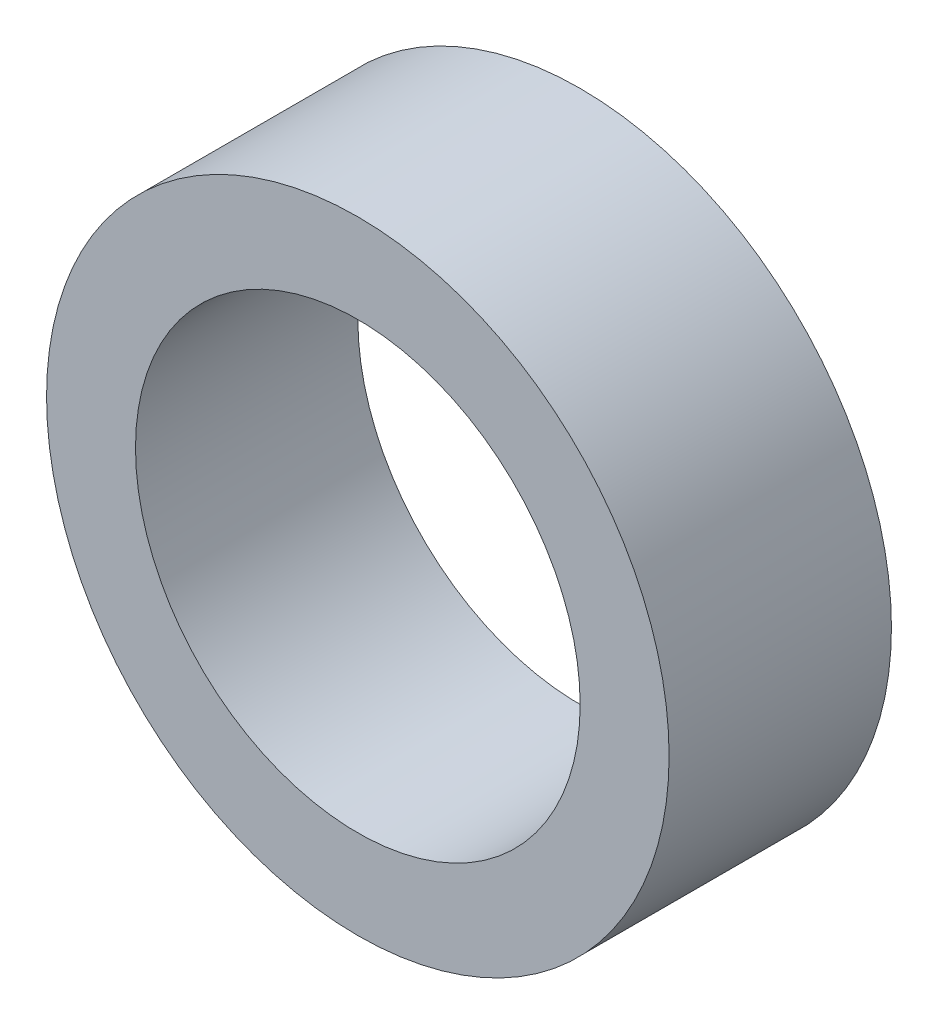
SolidWorks part; units mm, degrees
material "High-leaded brass, UNS C34200"
ref_plane "Front Plane" through (0, 0, 0) normal (0, 0, 1) x (1, 0, 0)
ref_plane "Top Plane" through (0, 0, 0) normal (0, 1, 0) x (1, 0, 0)
ref_plane "Right Plane" through (0, 0, 0) normal (1, 0, 0) x (0, 0, -1)
sketch "Sketch1" plane through (0, 0, 0) normal (0, 0, 1) x (1, 0, 0)
  circle A0 centre (0, 0) radius 3.5
  circle A1 centre (0, 0) radius 2.5
extrude "Boss-Extrude1" add sketch "Sketch1" along normal blind 2.5
